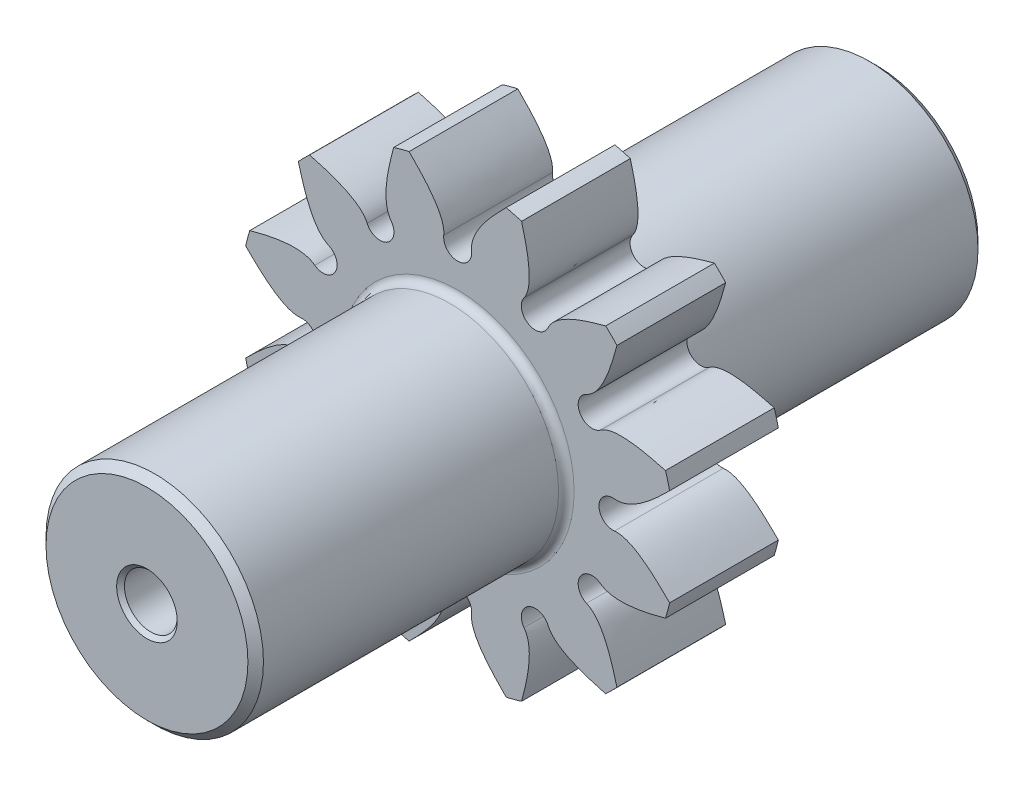
SolidWorks part; units mm, degrees
material "Acier INOX"
ref_plane "Plan de face" through (0, 0, 0) normal (0, 0, 1) x (1, 0, 0)
ref_plane "Plan de dessus" through (0, 0, 0) normal (0, 1, 0) x (1, 0, 0)
ref_plane "Plan de droite" through (0, 0, 0) normal (1, 0, 0) x (0, 0, -1)
sketch "Esquisse1" plane through (0, 0, 0) normal (0, 0, 1) x (1, 0, 0)
  circle A0 centre (0, 0) radius 14
  dimension "D1" = 28
extrude "Boss.-Extru.1" add sketch "Esquisse1" along normal mid plane 47
sketch "Esquisse2" plane through (0, 0, 23.5) normal (0, 0, 1) x (1, 0, 0)
  circle A0 centre (0, 0) radius 7
  circle A1 centre (0, 0) radius 14
  circle A2 centre (0, 0) radius 14 construction
  dimension "D1" = 14
extrude "Enlèv. mat.-Extru.1" cut sketch "Esquisse2" against normal blind 20
mirror "Symétrie1" about plane through (0, 0, 0) normal (0, 0, 1) of "Enlèv. mat.-Extru.1"
chamfer "Chanfrein1" distance 0.5 angle 45 2 edges at (7, 0, -23.5) (7, 0, 23.5)
sketch "Esquisse3" plane through (0, 0, -23.5) normal (0, 0, -1) x (-1, 0, 0)
  point P0 (0, 0)
hole_wizard "Dégagement M31" positions "Esquisse3D4" profile "Esquisse5" hole size "M3" standard "ISO"
sketch3d "Esquisse3D4"
  point P0 (0, 0, -23.5)
sketch "Esquisse5" plane through (0, 0, -23.5) normal (1, 0, 0) x (0, 1, 0)
  line L0 (0, 0) -> (0, 11.0215)
  line L1 (0, 11.0215) -> (1.7, 10)
  line L2 (1.7, 10) -> (1.7, 0)
  line L5 (1.7, 0) -> (0, 0)
  line L10 (0, 11.0215) -> (-1.7, 10) construction
  line L11 (0, -6.35) -> (0, 107.95) construction
  dimension "Diamètre du perçage" = 3.4
  dimension "Profondeur du perçage" = 10
  dimension "Angle de pointe" = 118
mirror "Symétrie3" about plane through (0, 0, 0) normal (0, 0, 1) of "Dégagement M31"
chamfer "Chanfrein2" distance 0.25 angle 45 2 edges at (-1.7, 0, -23.5) (1.7, 0, 23.5)
sketch "Esquisse6" plane through (0, 0, 3.5) normal (0, 0, 1) x (1, 0, 0)
  line L0 (0, 0) -> (0, 15.1804) construction
  arc A0 (-0.8944, 10.1) -> (0.8944, 10.1) centre (0, 10) ccw
  circle A1 centre (0, 0) radius 14 construction
  arc A2 (3.125, 13.6468) -> (-3.125, 13.6468) centre (0, 0) ccw
  spline S0 degree 3 poles (-3.125, 13.6468) (-2.5658, 13.0613) (-0.7528, 11.3667) (-0.8944, 10.1) knots 0 0 0 0 1 1 1 1
  spline S1 degree 3 poles (3.125, 13.6468) (2.5658, 13.0613) (0.7528, 11.3667) (0.8944, 10.1) knots 0 0 0 0 1 1 1 1
  dimension "D1" = 6.25
  dimension "D2" = 1.8
  dimension "D3" = 10
  dimension "D4" = 2.75
  dimension "D5" = 1.6
  dimension "D6" = 0.1
extrude "Enlèv. mat.-Extru.2" cut sketch "Esquisse6" against normal through all
pattern_circular "Répétition circulaire1" count 12 over 360 about axis through (0, 0, 3.5) along (0, 0, 1) of "Enlèv. mat.-Extru.2"
fillet "Congé1" radius 0.5 2 edges at (7, 0, -3.5) (7, 0, 3.5)
